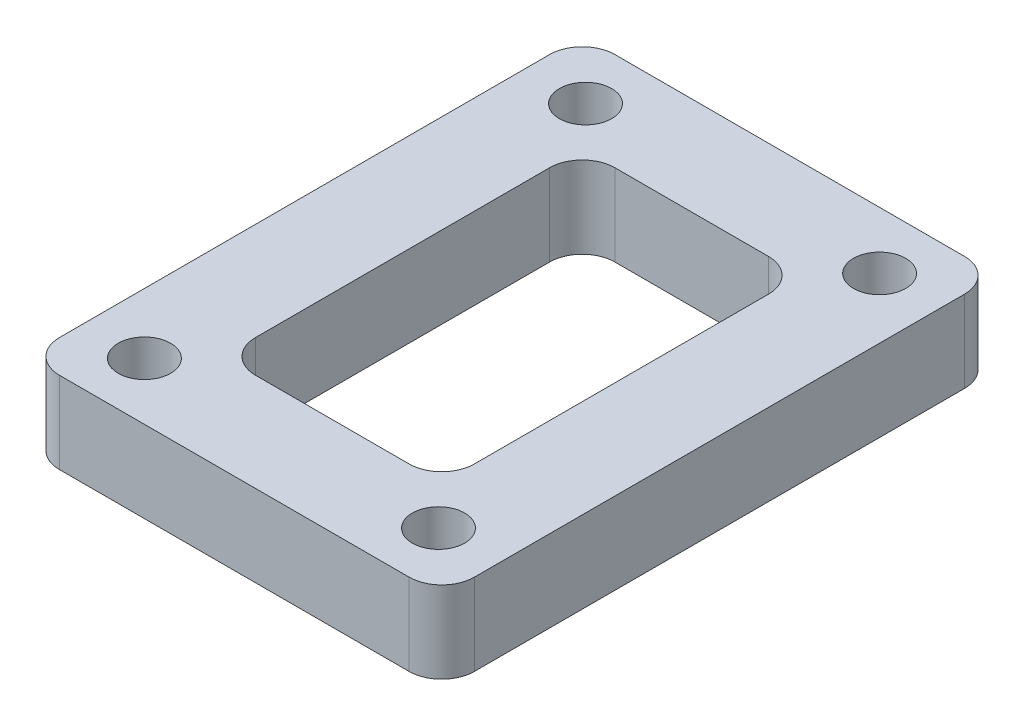
SolidWorks part; units mm, degrees
material "POM 乙缩醛共聚物"
ref_plane "前视基准面" through (0, 0, 0) normal (0, 0, 1) x (1, 0, 0)
ref_plane "上视基准面" through (0, 0, 0) normal (0, 1, 0) x (1, 0, 0)
ref_plane "右视基准面" through (0, 0, 0) normal (1, 0, 0) x (0, 0, -1)
sketch "草图1" plane through (0, 0, 0) normal (0, 1, 0) x (1, 0, 0)
  line L0 (0, 18.1129) -> (0, -15.9624) construction
  line L1 (-12.7, 17) -> (12.7, 17)
  line L2 (-12.7, 17) -> (-12.7, -17)
  line L3 (-12.7, -17) -> (12.7, -17)
  line L4 (12.7, 17) -> (12.7, -17)
  line L5 (-12.7, 17) -> (12.7, -17) construction
  line L6 (-12.7, -17) -> (12.7, 17) construction
  line L11 (-6.7, 11) -> (-6.7, -11)
  line L12 (-6.7, -11) -> (6.7, -11)
  line L13 (-24.7228, 0) -> (25.8526, 0) construction
  line L14 (6.7, 11) -> (6.7, -11)
  line L15 (-6.7, 11) -> (6.7, 11)
  circle A0 centre (-9, 13.5) radius 1.6
  circle A1 centre (9, 13.5) radius 1.6
  circle A2 centre (9, -13.5) radius 1.6
  circle A3 centre (-9, -13.5) radius 1.6
  point P0 (0, 0)
  point P5 (0, 0)
  dimension "D1" = 18
  dimension "D5" = 3.2
  dimension "D2" = 27
  dimension "D3" = 3.7
  dimension "D4" = 34
  dimension "D6" = 6
extrude "凸台-拉伸1" add sketch "草图1" along normal blind 5
fillet "圆角1" radius 2 8 edges at (-12.7, 2.5, -17) (12.7, 2.5, -17) (12.7, 2.5, 17) (6.7, 2.5, 11) (6.7, 2.5, -11) (-6.7, 2.5, -11) (-6.7, 2.5, 11) (-12.7, 2.5, 17)
